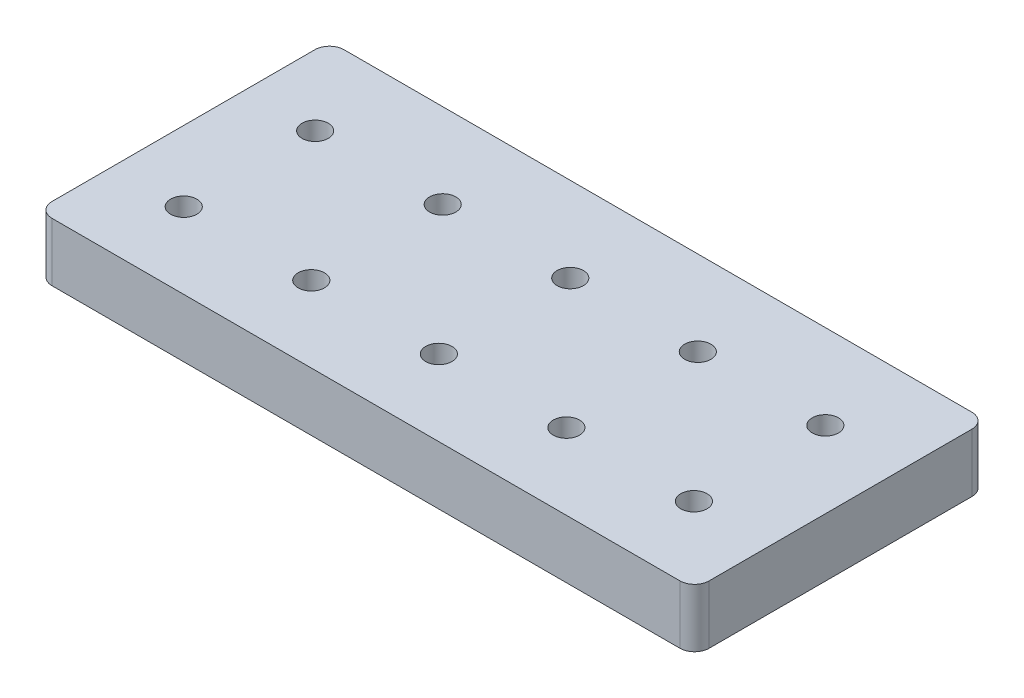
SolidWorks part; units mm, degrees
material "PVC Rigid"
ref_plane "Front Plane" through (0, 0, 0) normal (0, 0, 1) x (1, 0, 0)
ref_plane "Top Plane" through (0, 0, 0) normal (0, 1, 0) x (1, 0, 0)
ref_plane "Right Plane" through (0, 0, 0) normal (1, 0, 0) x (0, 0, -1)
sketch "Sketch1" plane through (0, 0, 0) normal (0, 1, 0) x (1, 0, 0)
  line L1 (-12.7, 0) -> (-558.8, 0)
  line L2 (0, 12.7) -> (0, 241.3)
  line L3 (-12.7, 254) -> (-558.8, 254)
  line L4 (-571.5, 12.7) -> (-571.5, 241.3)
  arc A0 (-12.7, 0) -> (0, 12.7) centre (-12.7, 12.7) ccw
  arc A1 (0, 241.3) -> (-12.7, 254) centre (-12.7, 241.3) ccw
  arc A2 (-558.8, 254) -> (-571.5, 241.3) centre (-558.8, 241.3) ccw
  arc A3 (-558.8, 0) -> (-571.5, 12.7) centre (-558.8, 12.7) cw
  point P7 (0, 0)
  dimension "D1" = 12.7
  dimension "D2" = 571.5
  dimension "D3" = 254
extrude "Boss-Extrude1" add sketch "Sketch1" along normal blind 50.8
sketch "Sketch2" plane through (0, 0, 0) normal (0, 1, 0) x (1, 0, 0)
  line L0 (0, 12.7) -> (-9.906, 12.7) construction
  line L1 (-571.5, 241.3) -> (-571.5, 12.7) construction
  line L2 (-510.286, 180.34) -> (-66.5708, 180.34) construction
  line L3 (0, 12.7) -> (0, 241.3) construction
  line L4 (-66.5708, 15.24) -> (-66.5708, 66.04) construction
  line L5 (-510.286, 66.04) -> (-66.5708, 66.04) construction
  line L6 (-510.286, 180.34) -> (-510.286, 66.04) construction
  line L7 (-66.5708, 66.04) -> (-66.5708, 180.34) construction
  circle A0 centre (-177.4996, 66.04) radius 50.8
  circle A1 centre (-66.5708, 66.04) radius 50.8
  circle A2 centre (-288.4284, 66.04) radius 50.8
  circle A3 centre (-399.3572, 66.04) radius 50.8
  circle A4 centre (-510.286, 66.04) radius 50.8
  circle A5 centre (-177.4996, 180.34) radius 50.8
  circle A6 centre (-288.4284, 180.34) radius 50.8
  circle A7 centre (-399.3572, 180.34) radius 50.8
  circle A8 centre (-510.286, 180.34) radius 50.8
  circle A9 centre (-66.5708, 180.34) radius 50.8
  dimension "D2" = 5
  dimension "D6" = 114.3
  dimension "D9" = 101.6
  dimension "D1" = 66.5708
  dimension "D5" = 9.906
  dimension "D3" = 2
  dimension "D7" = 61.214
  dimension "D8" = 443.7152
extrude "Cut-Extrude1" cut sketch "Sketch2" along normal blind 10.16
sketch "Sketch3" plane through (0, 10.16, 0) normal (0, -1, 0) x (1, 0, 0)
  line L0 (-66.5708, -129.54) -> (-66.5708, -116.84) construction
  line L1 (-66.5708, -123.19) -> (-571.5, -123.19) construction
  line L2 (-571.5, -241.3) -> (-571.5, -12.7) construction
  circle A0 centre (-66.5708, -180.34) radius 11.43
  circle A1 centre (-177.4996, -180.34) radius 11.43
  circle A2 centre (-288.4284, -180.34) radius 11.43
  circle A3 centre (-399.3572, -180.34) radius 11.43
  circle A4 centre (-510.286, -180.34) radius 11.43
  circle A5 centre (-66.5708, -180.34) radius 50.8 construction
  circle A6 centre (-66.5708, -180.34) radius 50.8 construction
  circle A7 centre (-66.5708, -66.04) radius 50.8 construction
  circle A8 centre (-510.286, -66.04) radius 11.43
  circle A9 centre (-399.3572, -66.04) radius 11.43
  circle A10 centre (-288.4284, -66.04) radius 11.43
  circle A11 centre (-177.4996, -66.04) radius 11.43
  circle A12 centre (-66.5708, -66.04) radius 11.43
  dimension "D1" = 22.86
extrude "Cut-Extrude2" cut sketch "Sketch3" against normal through all
sketch "Sketch6" plane through (0, 0, -254) normal (0, 0, -1) x (-1, 0, 0)
  line L0 (0, 0) -> (66.5708, 0) construction
  line L1 (12.7, 0) -> (558.8, 0) construction
  line L2 (66.5708, 0) -> (177.4996, 0) construction
  line L3 (177.4996, 0) -> (288.4284, 0) construction
  line L4 (288.4284, 0) -> (399.3572, 0) construction
  line L5 (399.3572, 0) -> (510.286, 0) construction
  dimension "D1" = 110.9288
  dimension "D2" = 66.5708
